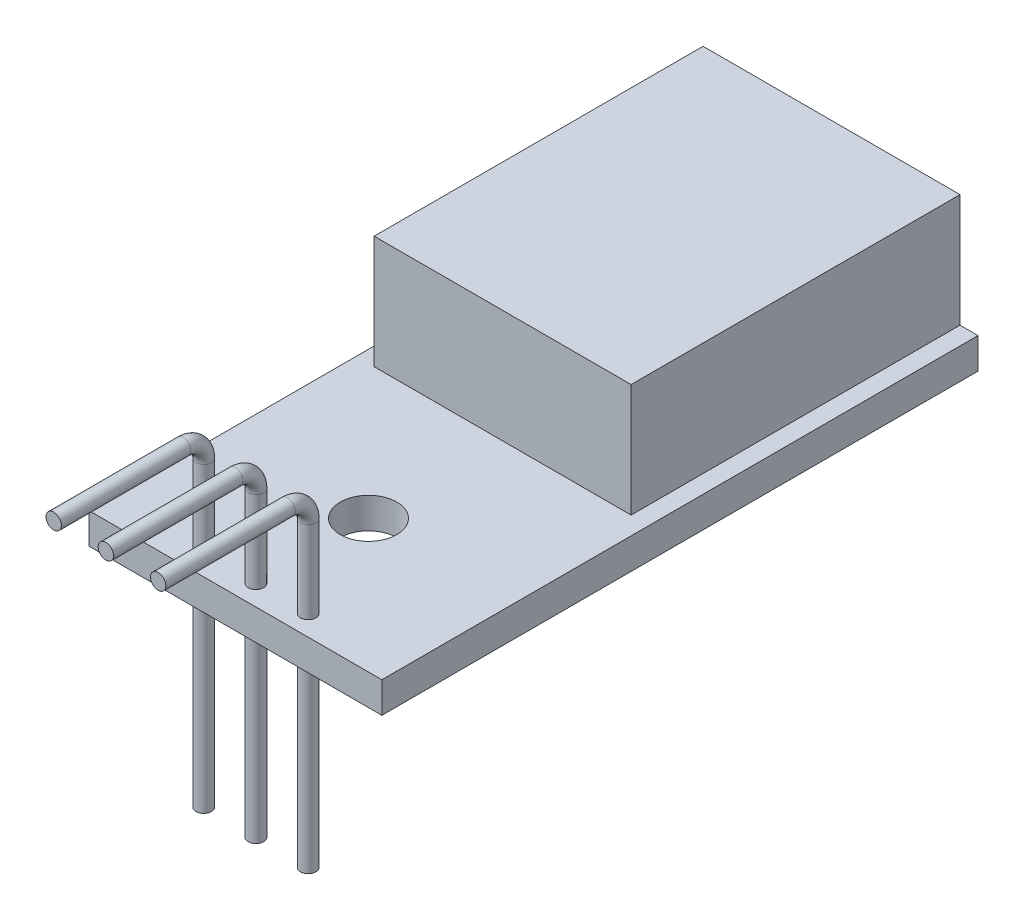
SolidWorks part; units mm, degrees
ref_plane "Front Plane" through (0, 0, 0) normal (0, 0, 1) x (1, 0, 0)
ref_plane "Top Plane" through (0, 0, 0) normal (0, 1, 0) x (1, 0, 0)
ref_plane "Right Plane" through (0, 0, 0) normal (1, 0, 0) x (0, 0, -1)
sketch "Sketch1" plane through (0, 0, 0) normal (0, 1, 0) x (1, 0, 0)
  line L0 (0, -9.4) -> (0, -14.5) construction
  line L1 (-7.125, -14.5) -> (7.125, -14.5)
  line L2 (-7.125, -14.5) -> (-7.125, 14.5)
  line L3 (-7.125, 14.5) -> (7.125, 14.5)
  line L4 (7.125, -14.5) -> (7.125, 14.5)
  line L5 (-7.125, -14.5) -> (7.125, 14.5) construction
  line L6 (-7.125, 14.5) -> (7.125, -14.5) construction
  circle A0 centre (0, -8.025) radius 1.375
  point P0 (0, 0)
  dimension "D3" = 2.75
  dimension "D1" = 14.25
  dimension "D2" = 29
  dimension "D4" = 5.1
extrude "Boss-Extrude1" add sketch "Sketch1" along normal blind 1.5
sketch "Sketch2" plane through (0, 1.5, 0) normal (0, 1, 0) x (1, 0, 0)
  line L0 (0, 14.5) -> (0, -14.5) construction
  line L1 (7.125, 14.5) -> (-7.125, 14.5) construction
  line L2 (-7.125, -14.5) -> (7.125, -14.5) construction
  line L4 (-6.25, -1.5) -> (6.25, -1.5)
  line L5 (-6.25, -1.5) -> (-6.25, 14.5)
  line L6 (-6.25, 14.5) -> (6.25, 14.5)
  line L7 (6.25, -1.5) -> (6.25, 14.5)
  line L8 (-6.25, -1.5) -> (6.25, 14.5) construction
  line L9 (-6.25, 14.5) -> (6.25, -1.5) construction
  point P6 (0, 6.5)
  dimension "D1" = 12.5
  dimension "D2" = 16
extrude "Boss-Extrude2" add sketch "Sketch2" along normal blind 5.5
ref_plane "Plane1" through (0, 0, 0) normal (-1, 0, 0) x (0, 0, 1)
sketch "Sketch3" plane through (0, 0, 0) normal (-1, 0, 0) x (0, 0, 1)
  line L0 (13.5, -1) -> (13.5, 5.5)
  line L1 (14.5, 6.5) -> (20.8, 6.5)
  line L2 (-14.5, 0) -> (14.5, 0) construction
  line L3 (14.5, 1.5) -> (14.5, 0) construction
  arc A0 (14.5, 6.5) -> (13.5, 5.5) centre (14.5, 5.5) ccw
  point P9 (13.5, 6.5)
  dimension "D5" = 1
  dimension "D1" = 7.5
  dimension "D2" = 1
  dimension "D3" = 7.3
  dimension "D4" = 1
ref_plane "Plane2" through (0, -1, 0) normal (0, -1, 0) x (-1, 0, 0)
sketch "Sketch4" plane through (0, -1, 0) normal (0, -1, 0) x (-1, 0, 0)
  circle A0 centre (0, -13.5) radius 0.375
  dimension "D1" = 0.75
sweep "Sweep1" add profiles "Sketch4" path "Sketch3"
pattern_linear "LPattern1" count 2 spacing 2.54 along (-1, 0, 0) count 2 spacing 2.54 along (1, 0, 0) of "Sweep1"
other "Move Face1" face at (2.54, -1, 13.125) face at (0, -1, 13.125) face at (-2.54, -1, 13.125) parameters "D1"=8.2
